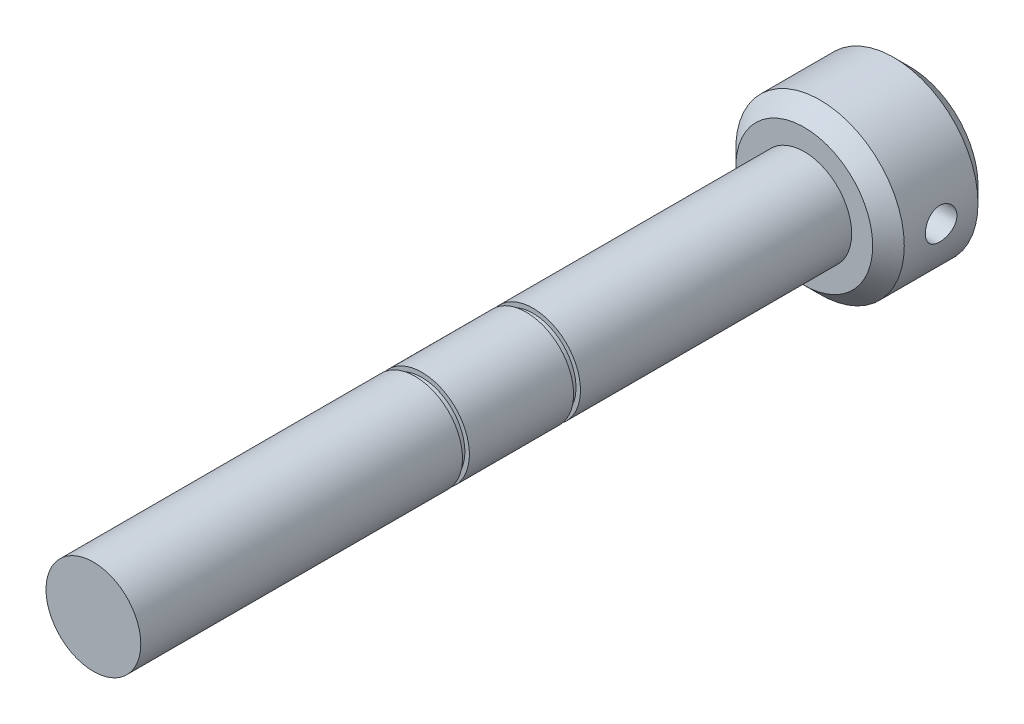
SolidWorks part; units mm, degrees
ref_plane "Front Plane" through (0, 0, 0) normal (0, 0, 1) x (1, 0, 0)
ref_plane "Top Plane" through (0, 0, 0) normal (0, 1, 0) x (1, 0, 0)
ref_plane "Right Plane" through (0, 0, 0) normal (1, 0, 0) x (0, 0, -1)
sketch "Sketch1" plane through (0, 0, 0) normal (0, 0, 1) x (1, 0, 0)
  circle A0 centre (0, 0) radius 16
  dimension "D1" = 32
extrude "Boss-Extrude1" add sketch "Sketch1" along normal blind 20
sketch "Sketch2" plane through (0, 0, 20) normal (0, 0, 1) x (1, 0, 0)
  circle A0 centre (0, 0) radius 9
  circle A1 centre (0, 0) radius 16
  circle A2 centre (0, 0) radius 16
  dimension "D2" = 18
  dimension "D1" = 0
extrude "Boss-Extrude2" add sketch "Sketch2" along normal blind 135 contours A0
cosmetic thread "Cosmetic Thread1" parameters "D2"=16.344
sketch "Sketch3" plane through (0, 0, 0) normal (1, 0, 0) x (0, 0, -1)
  line L0 (-20, 9) -> (-155, 9) construction
  line L1 (-72.8, 9) -> (-71.5, 9)
  line L2 (-72.8, 9) -> (-72.8, 8.15)
  line L3 (-72.8, 8.15) -> (-71.5, 8.15)
  line L4 (-71.5, 9) -> (-71.5, 8.15)
  line L6 (-93.9, 9) -> (-92.6, 9)
  line L7 (-93.9, 9) -> (-93.9, 8.15)
  line L8 (-93.9, 8.15) -> (-92.6, 8.15)
  line L9 (-92.6, 9) -> (-92.6, 8.15)
  line L10 (0, -16) -> (0, 16) construction
  line L11 (0, 0) -> (-123.2987, 0) construction
  dimension "D1" = 1.3
  dimension "D2" = 0.85
  dimension "D3" = 71.5
  dimension "D4" = 1.3
  dimension "D5" = 0.85
  dimension "D6" = 22.4
revolve "Cut-Revolve1" cut sketch "Sketch3" angle 360 about L11
sketch "Sketch4" plane through (0, 0, 0) normal (1, 0, 0) x (0, 0, -1)
  line L0 (-20, 16) -> (-20, -16) construction
  line L1 (-20, 16) -> (-20, -16)
  line L2 (0, 16) -> (-20, 16) construction
  line L3 (0, 16) -> (-20, 16)
  line L4 (0, -16) -> (0, 16) construction
  line L5 (0, -16) -> (0, 16)
  line L6 (-20, -16) -> (0, -16)
  line L7 (-20, 16) -> (0, -16)
  line L8 (0, 16) -> (-20, -16)
  circle A0 centre (-10, 0) radius 3
  dimension "D1" = 6
extrude "Cut-Extrude1" cut sketch "Sketch4" against normal through all both and the other way through all contours L7 A0 L8 | L7 A0 L8 | L8 A0 L7 | L8 A0 L7
chamfer "Chamfer1" distance 3 angle 45 2 edges at (16, 0, 0) (16, 0, 20)
